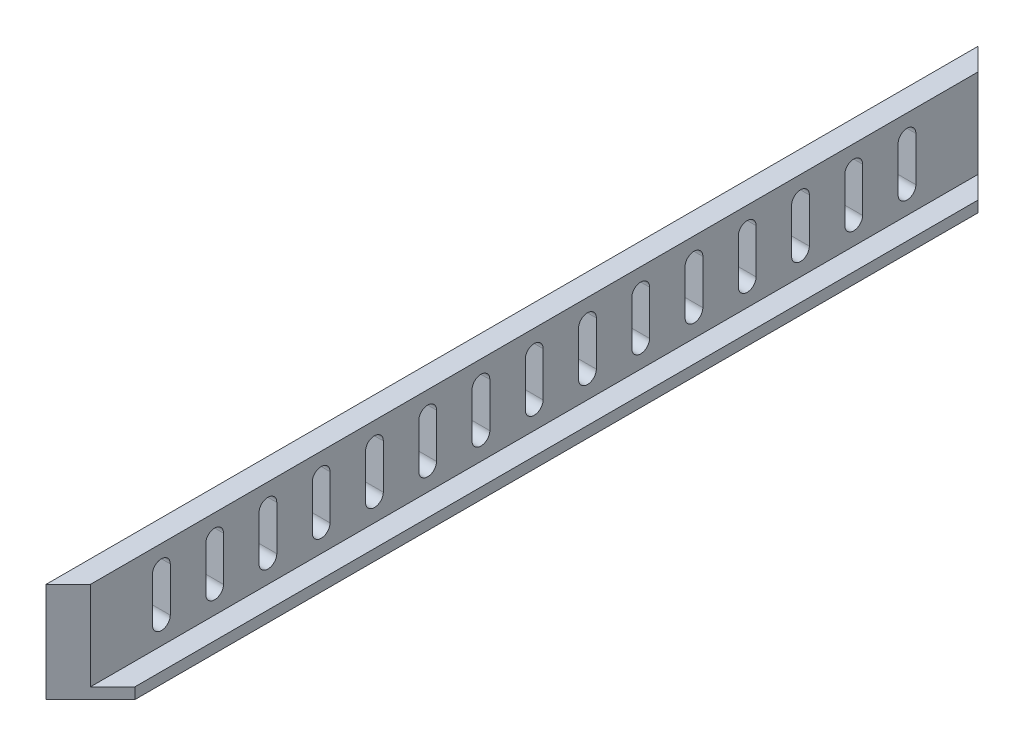
SolidWorks part; units mm, degrees
ref_plane "Plan de face" through (0, 0, 0) normal (0, 0, 1) x (1, 0, 0)
ref_plane "Plan de dessus" through (0, 0, 0) normal (0, 1, 0) x (1, 0, 0)
ref_plane "Plan de droite" through (0, 0, 0) normal (1, 0, 0) x (0, 0, -1)
sketch "Esquisse1" plane through (0, 0, 0) normal (0, 0, 1) x (1, 0, 0)
  line L0 (-10, 40) -> (-10, -5)
  line L1 (-10, -5) -> (10, -5)
  line L2 (10, -5) -> (10, 0)
  line L3 (10, 0) -> (0, 0)
  line L4 (0, 0) -> (0, 40)
  line L5 (0, 40) -> (-10, 40)
  dimension "D1" = 10
  dimension "D2" = 5
  dimension "D3" = 10
  dimension "D4" = 40
extrude "Boss.-Extru.1" add sketch "Esquisse1" along normal mid plane 600
sketch "Esquisse2" plane through (0, -5, 0) normal (0, -1, 0) x (1, 0, 0)
  line L0 (10, 190) -> (-10, 210)
  line L1 (10, 300) -> (10, -300) construction
  line L2 (-10, 300) -> (-10, -300) construction
  line L3 (-10, 210) -> (-10, 300)
  line L4 (-10, 300) -> (10, 300)
  line L5 (10, 300) -> (10, 190)
  line L6 (0, 300) -> (0, -300) construction
  point P6 (0, 200)
  dimension "D1" = 200
  dimension "D2" = 45
extrude "Enlèv. mat.-Extru.1" cut sketch "Esquisse2" against normal through all both and the other way through all
mirror "Symétrie1" about plane through (0, 0, 0) normal (0, 0, 1) of "Enlèv. mat.-Extru.1"
sketch "Esquisse3" plane through (0, 0, 0) normal (1, 0, 0) x (0, 0, -1)
  line L0 (0, 10) -> (0, 30) construction
  line L5 (-4, 10) -> (-4, 30)
  line L6 (4, 10) -> (4, 30)
  line L7 (-200, 40) -> (200, 40) construction
  line L10 (-200, 0) -> (200, 0) construction
  arc A0 (-4, 10) -> (4, 10) centre (0, 10) ccw
  arc A1 (4, 30) -> (-4, 30) centre (0, 30) ccw
  point P2 (0, 20)
  dimension "D1" = 4
  dimension "D2" = 10
  dimension "D3" = 10
extrude "Enlèv. mat.-Extru.2" cut sketch "Esquisse3" against normal through all both and the other way through all
pattern_linear "Répétition linéaire1" count 8 spacing 24 along (0, 0, 1) count 8 spacing 24 along (0, 0, -1) of "Enlèv. mat.-Extru.2"
